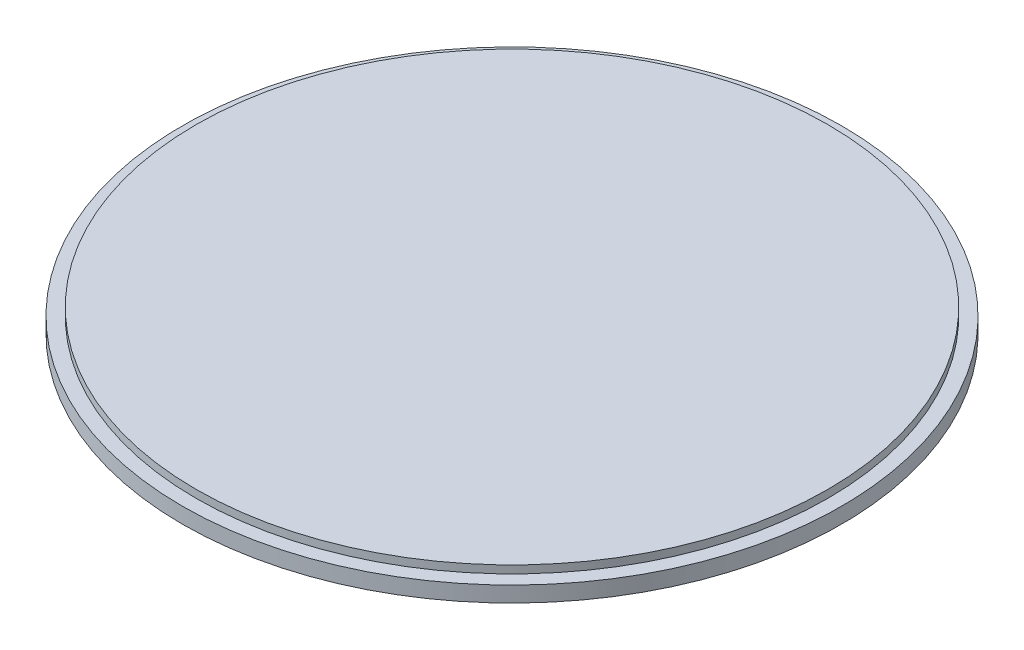
SolidWorks part; units mm, degrees
ref_plane "Front Plane" through (0, 0, 0) normal (0, 0, 1) x (1, 0, 0)
ref_plane "Top Plane" through (0, 0, 0) normal (0, 1, 0) x (1, 0, 0)
ref_plane "Right Plane" through (0, 0, 0) normal (1, 0, 0) x (0, 0, -1)
sketch "Sketch1" plane through (0, 0, 0) normal (0, 1, 0) x (1, 0, 0)
  circle A0 centre (0, 0) radius 16.9
  dimension "D1" = 33.8
extrude "Boss-Extrude1" add sketch "Sketch1" along normal blind 0.8
sketch "Sketch2" plane through (0, 0.8, 0) normal (0, 1, 0) x (1, 0, 0)
  circle A0 centre (0, 0) radius 16.2
  dimension "D1" = 32.4
extrude "Boss-Extrude2" add sketch "Sketch2" along normal blind 0.4
